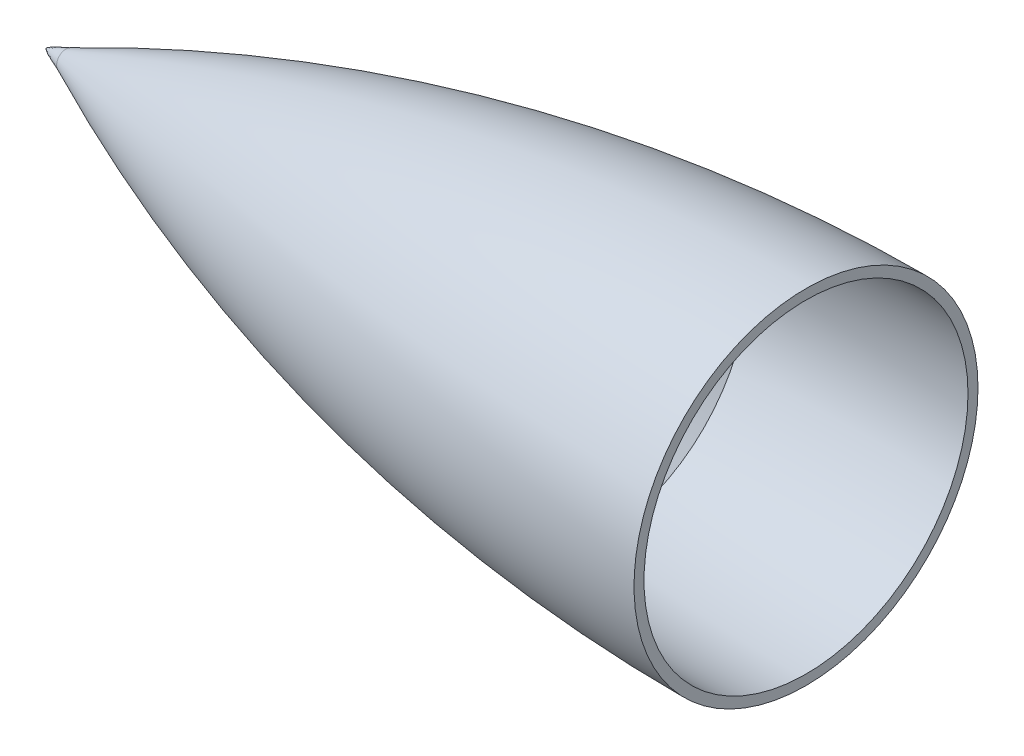
SolidWorks part; units mm, degrees
ref_plane "Front Plane" through (0, 0, 0) normal (0, 0, 1) x (1, 0, 0)
ref_plane "Top Plane" through (0, 0, 0) normal (0, 1, 0) x (1, 0, 0)
ref_plane "Right Plane" through (0, 0, 0) normal (1, 0, 0) x (0, 0, -1)
sketch "Sketch2" plane through (0, 0, 0) normal (0, 0, 1) x (1, 0, 0)
  line L0 (0, 441.2674) -> (0, 438.7674) construction
  line L1 (0, 441.2674) -> (0, 438.7674)
  line L2 (-178.0795, 398.2674) -> (-190, 398.2674)
  line L12 (-53.4361, 434.239) -> (-53.4361, 438.02) construction
  line L20 (-190, 398.2674) -> (-231.9218, 398.2674) construction
  line L21 (-190, 398.2674) -> (-178.0795, 398.2674) construction
  line L23 (-51.9999, 435.6752) -> (-54.8722, 432.8029)
  arc A0 (0, 441.2674) -> (-190, 398.2674) centre (0, 0) ccw
  arc A3 (0, 438.7674) -> (-51.9999, 435.6752) centre (0, 0) ccw
  arc A8 (-54.8722, 432.8029) -> (-178.0795, 398.2674) centre (0, 0) ccw
  dimension "D1" = 190
  dimension "D3" = 5
  dimension "D4" = 11.9205
  dimension "D2" = 2.5
  dimension "D5" = 45
revolve "Revolve3" add sketch "Sketch2" angle 360 about L20
sketch "Sketch3" plane through (0, 0, 0) normal (0, 0, 1) x (1, 0, 0)
  line L0 (-190, 398.2674) -> (-185, 398.2674)
  line L1 (-185, 398.2674) -> (-185, 400.6145)
  arc A0 (0, 441.2674) -> (-190, 398.2674) centre (0, 0) ccw construction
  arc A1 (-185, 400.6145) -> (-190, 398.2674) centre (0, 0) ccw
  dimension "D1" = 5
revolve "Cut-Revolve3" cut sketch "Sketch3" angle 360 about L0
sketch "Sketch4" plane through (0, 0, 0) normal (0, 0, 1) x (1, 0, 0)
  line L0 (-185, 398.2674) -> (-189.991, 398.2674)
  line L2 (2.5, -1.1735) -> (-2.5, -1.1735)
  line L3 (2.5, -1.1735) -> (2.5, 1.1735)
  line L4 (2.5, -1.1735) -> (-2.5, -1.1735)
  line L5 (2.5, -1.1735) -> (2.5, 1.1735)
  line L8 (-185, 400.6145) -> (-185, 395.9204) construction
  line L9 (-185, 398.2674) -> (-185, 400.6145)
  spline S0 degree 3 poles (2.5, 1.1735) (-0.7043, -0.033) (-2.4355, -0.6033) (-2.5, -1.1735) knots 0 0 0 0 0.5 0.5 0.5 0.5
  spline S1 degree 3 poles (2.5, 1.1735) (-0.7043, -0.033) (-2.4355, -0.6033) (-2.5, -1.1735) knots 0 0 0 0 0.5 0.5 0.5 0.5
  spline S2 degree 3 poles (-185, 400.6145) (-186.9943, 399.7724) (-189.3345, 399.0591) (-189.991, 398.2674) knots 0 0 0 0 1 1 1 1
  dimension "D2" = 5
  dimension "D3" = 5
revolve "Revolve4" add sketch "Sketch4" angle 360 about L0
